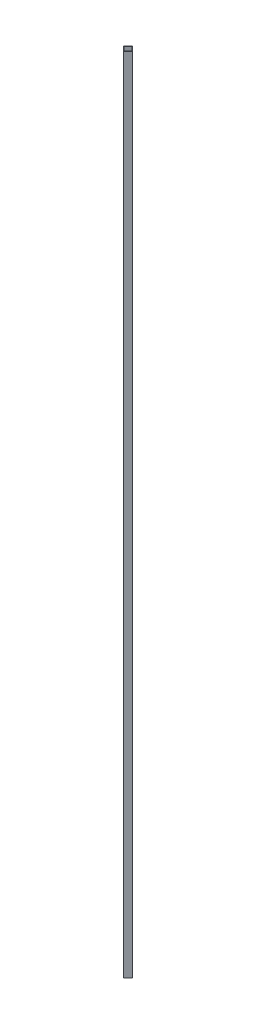
SolidWorks part; units mm, degrees
ref_plane "Front Plane" through (0, 0, 0) normal (0, 0, 1) x (1, 0, 0)
ref_plane "Top Plane" through (0, 0, 0) normal (0, 1, 0) x (1, 0, 0)
ref_plane "Right Plane" through (0, 0, 0) normal (1, 0, 0) x (0, 0, -1)
sketch "Sketch1" plane through (0, 0, 0) normal (0, 1, 0) x (1, 0, 0)
  line L1 (-17.9605, 0) -> (0, 17.9605)
  line L2 (-17.9605, 0) -> (0, -17.9605)
  line L3 (0, -17.9605) -> (17.9605, 0)
  line L4 (0, 17.9605) -> (17.9605, 0)
  line L5 (-17.9605, 0) -> (17.9605, 0) construction
  line L6 (0, -17.9605) -> (0, 17.9605) construction
  line L7 (0, -15.6978) -> (15.6978, 0)
  line L8 (0, -15.6978) -> (-15.6978, 0)
  line L9 (-15.6978, 0) -> (0, 15.6978)
  line L10 (15.6978, 0) -> (0, 15.6978)
  line L11 (0, -15.6978) -> (0, 15.6978) construction
  line L12 (-15.6978, 0) -> (15.6978, 0) construction
  point P0 (0, 0)
  point P6 (0, 0)
  point P14 (0, 0)
  point P15 (0, 0)
  point P16 (-17.9605, -17.9605)
  point P17 (17.9605, -17.9605)
  dimension "D4" = 1.6
  dimension "D8" = 1.6
  dimension "D1" = 25.4
  dimension "D2" = 25.4
  dimension "D3" = 1.6
  dimension "D5" = 1.6
  dimension "D6" = 90
  dimension "D7" = 90
  dimension "D9" = 270
extrude "Boss-Extrude1" add sketch "Sketch1" along normal blind 3048 contours L1 L4 L3 L2 | L9 L10 L7 L8
